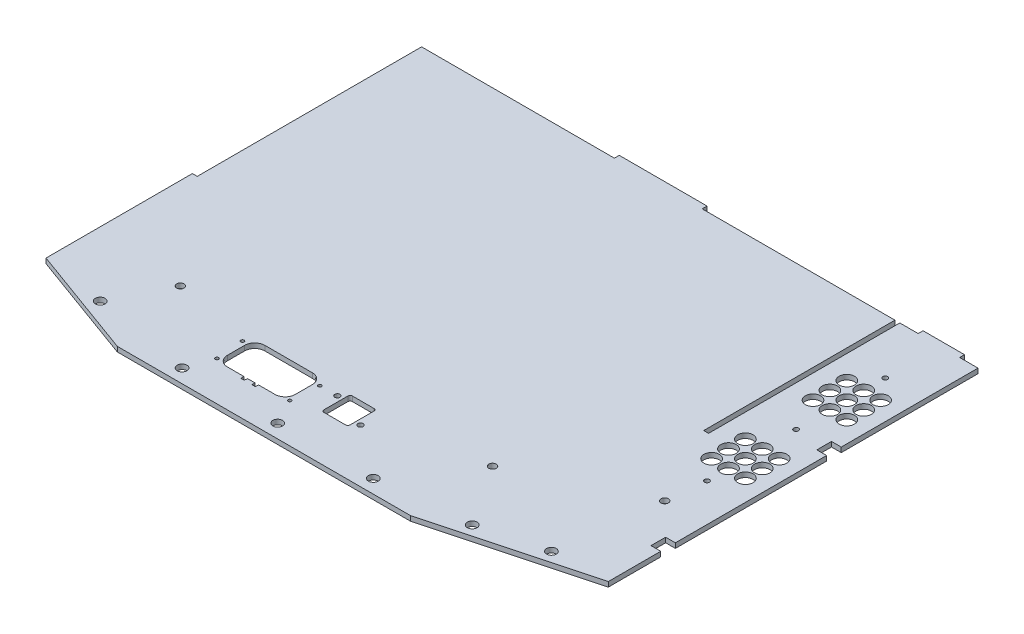
SolidWorks part; units mm, degrees
material "6061-T6 (SS)"
ref_plane "X-Y Datum" through (0, 0, 0) normal (0, 0, 1) x (1, 0, 0)
ref_plane "X-Z Datum" through (0, 0, 0) normal (0, 1, 0) x (1, 0, 0)
ref_plane "Y-Z Datum" through (0, 0, 0) normal (1, 0, 0) x (0, 0, -1)
sketch "Sketch1" plane through (0, 0, 0) normal (0, 0, 1) x (1, 0, 0)
  line L1 (-154.0408, -1.5875) -> (154.0408, -1.5875)
  line L2 (-154.0408, -1.5875) -> (-154.0408, 1.5875)
  line L3 (-154.0408, 1.5875) -> (154.0408, 1.5875)
  line L4 (154.0408, -1.5875) -> (154.0408, 1.5875)
  line L5 (-154.0408, -1.5875) -> (154.0408, 1.5875) construction
  line L6 (-154.0408, 1.5875) -> (154.0408, -1.5875) construction
  point P0 (0, 0)
  dimension "D1" = 3.175
  dimension "D2" = 308.0817
extrude "Boss-Extrude1" add sketch "Sketch1" along normal blind 267.83
sketch "Sketch3" plane through (154.0408, 0, 0) normal (1, 0, 0) x (0, 0, -1)
  line L9 (0, -1.5875) -> (0, 1.5875)
  line L10 (0, 1.5875) -> (-267.83, 1.5875)
  line L11 (-267.83, 1.5875) -> (-267.83, -1.5875)
  line L12 (-267.83, -1.5875) -> (0, -1.5875)
  line L13 (0, -1.5875) -> (0, 1.5875)
  line L14 (0, 1.5875) -> (-267.83, 1.5875)
  line L15 (-267.83, 1.5875) -> (-267.83, -1.5875)
  line L16 (-267.83, -1.5875) -> (0, -1.5875)
  dimension "D1" = 0
extrude "Boss-Extrude3" add sketch "Sketch3" along normal blind 3.175
sketch "Sketch4" plane through (0, 0, 267.83) normal (0, 0, 1) x (1, 0, 0)
  line L1 (157.2158, -1.5875) -> (208.1047, -1.5875)
  line L2 (157.2158, -1.5875) -> (157.2158, 1.5875)
  line L3 (157.2158, 1.5875) -> (208.1047, 1.5875)
  line L4 (208.1047, -1.5875) -> (208.1047, 1.5875)
  dimension "D1" = 3.175
  dimension "D2" = 50.8889
extrude "Boss-Extrude4" add sketch "Sketch4" against normal blind 267.83
sketch "Sketch6" plane through (0, 1.5875, 0) normal (0, 1, 0) x (1, 0, 0)
  line L0 (106.5047, -267.83) -> (106.5047, -228.46)
  line L1 (208.1047, -267.83) -> (-154.0408, -267.83) construction
  line L2 (208.1047, -228.46) -> (106.5047, -228.46)
  line L3 (208.1047, 0) -> (208.1047, -267.83) construction
  line L5 (106.5047, -267.83) -> (208.1047, -240.6064)
  line L7 (208.1047, -228.46) -> (208.1047, -240.6064)
  line L8 (208.1047, 0) -> (208.1047, -267.83) construction
  line L9 (208.1047, -267.83) -> (-154.0408, -267.83) construction
  line M9 (-154.0408, -267.83) -> (208.1047, -267.83)
  line M10 (208.1047, -267.83) -> (208.1047, 0)
  dimension "D1" = 39.37
  dimension "D2" = 101.6
  dimension "D3" = 15
extrude "Cut-Extrude1" cut sketch "Sketch6" against normal through all contours L5 M9 M10
sketch "Sketch19" plane through (0, 1.5875, 0) normal (0, 1, 0) x (1, 0, 0)
  line L0 (208.1047, 0) -> (208.1047, -240.6064) construction
  line L1 (208.1047, 0) -> (-154.0408, 0) construction
  line L3 (164.1047, -82.5) -> (204.1047, -82.5)
  line L4 (164.1047, -82.5) -> (164.1047, -42.5)
  line L5 (164.1047, -42.5) -> (204.1047, -42.5)
  line L6 (204.1047, -82.5) -> (204.1047, -42.5)
  line L7 (164.1047, -82.5) -> (204.1047, -42.5) construction
  line L8 (164.1047, -42.5) -> (204.1047, -82.5) construction
  circle A0 centre (172.4867, -49.7748) radius 5
  dimension "D5" = 10
  dimension "D6" = 7.2748
  dimension "D1" = 40
  dimension "D2" = 40
  dimension "D3" = 42.5
  dimension "D4" = 8.382
  dimension "D7" = 4
extrude "Cut-Extrude5" cut sketch "Sketch19" against normal through all contours A0
pattern_linear "LPattern1" count 3 spacing 11 along (1, 0, 0) of "Cut-Extrude5"
pattern_linear "LPattern2" count 3 spacing 11 along (0, 0, 1) of "LPattern1", "Cut-Extrude5"
pattern_linear "LPattern3" count 2 spacing 66 along (0, 0, 1) of "LPattern2", "Cut-Extrude5", "LPattern1"
sketch "Sketch21" plane through (-154.0408, 0, 0) normal (-1, 0, 0) x (0, 0, 1)
  line L14 (0, -1.5875) -> (267.83, -1.5875)
  line L15 (267.83, -1.5875) -> (267.83, 1.5875)
  line L16 (267.83, 1.5875) -> (0, 1.5875)
  line L17 (0, 1.5875) -> (0, -1.5875)
  line L18 (0, -1.5875) -> (267.83, -1.5875)
  line L20 (267.83, 1.5875) -> (0, 1.5875)
  line L21 (0, 1.5875) -> (0, -1.5875)
  line L22 (267.83, -1.5875) -> (267.83, 1.5875)
  dimension "D1" = 0
extrude "Boss-Extrude5" add sketch "Sketch21" along normal blind 3.175
sketch "Sketch11" plane through (0, -1.5875, 0) normal (0, -1, 0) x (1, 0, 0)
  line L0 (-84.2547, 267.83) -> (-84.2547, 241.2743)
  line L3 (-157.2158, 267.83) -> (106.5047, 267.83) construction
  line L4 (-157.2158, 241.2743) -> (-84.2547, 267.83)
  line L5 (-157.2158, 241.2743) -> (-84.2547, 241.2743)
  line L7 (-157.2158, 0) -> (-157.2158, 267.83) construction
  dimension "D1" = 26.5557
  dimension "D2" = 20
extrude "Cut-Extrude3" cut sketch "Sketch11" against normal through all
sketch "Sketch36" plane through (0, 1.5875, 0) normal (0, 1, 0) x (1, 0, 0)
  circle A1 centre (183.4867, -35.7748) radius 2.4 construction
  circle A2 centre (183.4867, -35.7748) radius 1.5875
  dimension "D1" = 3.175
extrude "Cut-Extrude12" cut sketch "Sketch36" against normal through all both and the other way through all
pattern_linear "LPattern4" count 3 spacing 58 along (0, 0, 1) of "Cut-Extrude12"
sketch "Sketch38" plane through (0, 1.5875, 0) normal (0, 1, 0) x (1, 0, 0)
  point P0 (180.965, -176.776)
  point P1 (105.4291, -213.285)
  point P2 (105.4291, -213.285)
  point P3 (-97.7709, -213.285)
hole_wizard "M4 Clearance Hole1" positions "Sketch38" profile "Sketch39" hole size "M4" standard "ANSI Metric" end condition through all
sketch "Sketch39" plane through (180.965, 1.5875, 176.776) normal (1, 0, 0) x (0, 0, 1)
  line L0 (0, 0) -> (0, 3.175)
  line L1 (0, 3.175) -> (2.4, 3.175)
  line L2 (2.4, 3.175) -> (2.4, 0)
  line L5 (2.4, 0) -> (0, 0)
  line L11 (0, -6.35) -> (0, 107.95) construction
  dimension "Thru Hole Dia." = 4.8
  dimension "Thru Hole Depth" = 3.175
sketch "Sketch40" plane through (0, 1.5875, 0) normal (0, 1, 0) x (1, 0, 0)
  circle A0 centre (172.5447, -242.093) radius 3.175
  circle A1 centre (131.9047, -252.9824) radius 3.175
  circle A2 centre (73.4847, -258.94) radius 3.175
  circle A3 centre (11.2547, -258.94) radius 3.175
  circle A4 centre (-50.9753, -258.94) radius 3.175
  circle A5 centre (-115.3222, -247.9214) radius 3.175
  point P0 (-115.3222, -247.9214)
  point P1 (-50.9753, -258.94)
  point P3 (11.2547, -258.94)
  point P5 (73.4847, -258.94)
  point P7 (131.9047, -252.9824)
  point P9 (172.5447, -242.093)
  dimension "D1" = 6.35
extrude "Cut-Extrude13" cut sketch "Sketch40" against normal through all
sketch "Sketch41" plane through (0, 1.5875, 0) normal (0, 1, 0) x (1, 0, 0)
  line L0 (-25.8051, -243.2308) -> (-25.6301, -245.2308) construction
  line L1 (-25.6301, -245.2308) -> (-24.1801, -245.2308) construction
  line L2 (-24.1801, -245.2308) -> (-24.0051, -243.2308) construction
  line L3 (-18.4301, -245.2308) -> (-16.9801, -245.2308) construction
  line L4 (-16.9801, -245.2308) -> (-16.8051, -243.2308) construction
  line L5 (-18.6051, -243.2308) -> (-18.4301, -245.2308) construction
  line L6 (-16.8051, -243.2308) -> (-5.8051, -243.2308) construction
  line L7 (0.3949, -237.0308) -> (0.3949, -225.8308) construction
  line L8 (-5.8051, -219.6308) -> (-36.8051, -219.6308) construction
  line L9 (-43.0051, -225.8308) -> (-43.0051, -237.0308) construction
  line L10 (-36.8051, -243.2308) -> (-25.8051, -243.2308) construction
  line L11 (-24.0051, -243.2308) -> (-18.6051, -243.2308) construction
  line L12 (-25.8051, -243.2308) -> (-25.6301, -245.2308) construction
  line L13 (-25.6301, -245.2308) -> (-24.1801, -245.2308) construction
  line L14 (-24.1801, -245.2308) -> (-24.0051, -243.2308) construction
  line L15 (-18.4301, -245.2308) -> (-16.9801, -245.2308) construction
  line L16 (-16.9801, -245.2308) -> (-16.8051, -243.2308) construction
  line L17 (-18.6051, -243.2308) -> (-18.4301, -245.2308) construction
  line L18 (-16.8051, -243.2308) -> (-5.8051, -243.2308) construction
  line L19 (0.3949, -237.0308) -> (0.3949, -225.8308) construction
  line L20 (-5.8051, -219.6308) -> (-36.8051, -219.6308) construction
  line L21 (-43.0051, -225.8308) -> (-43.0051, -237.0308) construction
  line L22 (-36.8051, -243.2308) -> (-25.8051, -243.2308) construction
  line L23 (-24.0051, -243.2308) -> (-18.6051, -243.2308) construction
  line L24 (20.242, -220.3508) -> (34.292, -220.3508) construction
  line L25 (34.292, -219.7008) -> (20.242, -219.7008) construction
  line L26 (19.142, -220.8008) -> (19.142, -236.3508) construction
  line L27 (19.792, -236.3508) -> (19.792, -220.8008) construction
  line L28 (20.242, -237.4508) -> (34.292, -237.4508) construction
  line L29 (34.292, -236.8008) -> (20.242, -236.8008) construction
  line L30 (34.742, -220.8008) -> (34.742, -236.3508) construction
  line L31 (35.392, -236.3508) -> (35.392, -220.8008) construction
  line L32 (20.242, -220.3508) -> (34.292, -220.3508) construction
  line L33 (34.292, -219.7008) -> (20.242, -219.7008) construction
  line L34 (19.142, -220.8008) -> (19.142, -236.3508) construction
  line L35 (19.792, -236.3508) -> (19.792, -220.8008) construction
  line L36 (20.242, -237.4508) -> (34.292, -237.4508) construction
  line L37 (34.292, -236.8008) -> (20.242, -236.8008) construction
  line L38 (34.742, -220.8008) -> (34.742, -236.3508) construction
  line L39 (35.392, -236.3508) -> (35.392, -220.8008) construction
  line L40 (15.267, -225.0758) -> (15.267, -223.0758) construction
  line L41 (39.267, -234.0758) -> (39.267, -232.0758) construction
  line L42 (-26.1542, -243.6118) -> (-25.9792, -245.6118)
  line L43 (-25.9792, -245.6118) -> (-23.8309, -245.6118)
  line L44 (-23.8309, -245.6118) -> (-23.656, -243.6118)
  line L45 (-23.656, -243.6118) -> (-18.9542, -243.6118)
  line L46 (-18.9542, -243.6118) -> (-18.7792, -245.6118)
  line L47 (-18.7792, -245.6118) -> (-16.6309, -245.6118)
  line L48 (-16.6309, -245.6118) -> (-16.456, -243.6118)
  line L49 (-16.456, -243.6118) -> (-5.8051, -243.6118)
  line L50 (0.7759, -237.0308) -> (0.7759, -225.8308)
  line L51 (-5.8051, -219.2498) -> (-36.8051, -219.2498)
  line L52 (-43.3861, -225.8308) -> (-43.3861, -237.0308)
  line L53 (-36.8051, -243.6118) -> (-26.1542, -243.6118)
  line L54 (18.761, -220.8008) -> (18.761, -236.3508)
  line L55 (20.242, -237.8318) -> (34.292, -237.8318)
  line L56 (35.773, -236.3508) -> (35.773, -220.8008)
  line L57 (34.292, -219.3198) -> (20.242, -219.3198)
  spline S0 degree 3 poles (-5.8051, -243.2308) (-2.1732, -243.2308) (0.3949, -240.6627) (0.3949, -237.0308) knots 0 0 0 0 1 1 1 1 weights 1 0.804738 0.804738 1 construction
  spline S1 degree 3 poles (0.3949, -225.8308) (0.3949, -222.1989) (-2.1732, -219.6308) (-5.8051, -219.6308) knots 0 0 0 0 1 1 1 1 weights 1 0.804738 0.804738 1 construction
  spline S2 degree 3 poles (-36.8051, -219.6308) (-40.4369, -219.6308) (-43.0051, -222.1989) (-43.0051, -225.8308) knots 0 0 0 0 1 1 1 1 weights 1 0.804738 0.804738 1 construction
  spline S3 degree 3 poles (-43.0051, -237.0308) (-43.0051, -240.6627) (-40.4369, -243.2308) (-36.8051, -243.2308) knots 0 0 0 0 1 1 1 1 weights 1 0.804738 0.804738 1 construction
  spline S4 degree 3 poles (-5.8051, -243.2308) (-2.1732, -243.2308) (0.3949, -240.6627) (0.3949, -237.0308) knots 0 0 0 0 1 1 1 1 weights 1 0.804738 0.804738 1 construction
  spline S5 degree 3 poles (0.3949, -225.8308) (0.3949, -222.1989) (-2.1732, -219.6308) (-5.8051, -219.6308) knots 0 0 0 0 1 1 1 1 weights 1 0.804738 0.804738 1 construction
  spline S6 degree 3 poles (-36.8051, -219.6308) (-40.4369, -219.6308) (-43.0051, -222.1989) (-43.0051, -225.8308) knots 0 0 0 0 1 1 1 1 weights 1 0.804738 0.804738 1 construction
  spline S7 degree 3 poles (-43.0051, -237.0308) (-43.0051, -240.6627) (-40.4369, -243.2308) (-36.8051, -243.2308) knots 0 0 0 0 1 1 1 1 weights 1 0.804738 0.804738 1 construction
  spline S8 degree 3 poles (34.292, -220.3508) (34.5556, -220.3508) (34.742, -220.5372) (34.742, -220.8008) knots 0 0 0 0 1 1 1 1 weights 1 0.804738 0.804738 1 construction
  spline S9 degree 3 poles (35.392, -220.8008) (35.392, -220.1564) (34.9364, -219.7008) (34.292, -219.7008) knots 0 0 0 0 1 1 1 1 weights 1 0.804738 0.804738 1 construction
  spline S10 degree 3 poles (20.242, -219.7008) (19.5976, -219.7008) (19.142, -220.1564) (19.142, -220.8008) knots 0 0 0 0 1 1 1 1 weights 1 0.804738 0.804738 1 construction
  spline S11 degree 3 poles (19.792, -220.8008) (19.792, -220.5372) (19.9784, -220.3508) (20.242, -220.3508) knots 0 0 0 0 1 1 1 1 weights 1 0.804738 0.804738 1 construction
  spline S12 degree 3 poles (19.142, -236.3508) (19.142, -236.9952) (19.5976, -237.4508) (20.242, -237.4508) knots 0 0 0 0 1 1 1 1 weights 1 0.804738 0.804738 1 construction
  spline S13 degree 3 poles (20.242, -236.8008) (19.9784, -236.8008) (19.792, -236.6144) (19.792, -236.3508) knots 0 0 0 0 1 1 1 1 weights 1 0.804738 0.804738 1 construction
  spline S14 degree 3 poles (34.292, -237.4508) (34.9364, -237.4508) (35.392, -236.9952) (35.392, -236.3508) knots 0 0 0 0 1 1 1 1 weights 1 0.804738 0.804738 1 construction
  spline S15 degree 3 poles (34.742, -236.3508) (34.742, -236.6144) (34.5556, -236.8008) (34.292, -236.8008) knots 0 0 0 0 1 1 1 1 weights 1 0.804738 0.804738 1 construction
  spline S16 degree 3 poles (34.292, -220.3508) (34.5556, -220.3508) (34.742, -220.5372) (34.742, -220.8008) knots 0 0 0 0 1 1 1 1 weights 1 0.804738 0.804738 1 construction
  spline S17 degree 3 poles (35.392, -220.8008) (35.392, -220.1564) (34.9364, -219.7008) (34.292, -219.7008) knots 0 0 0 0 1 1 1 1 weights 1 0.804738 0.804738 1 construction
  spline S18 degree 3 poles (20.242, -219.7008) (19.5976, -219.7008) (19.142, -220.1564) (19.142, -220.8008) knots 0 0 0 0 1 1 1 1 weights 1 0.804738 0.804738 1 construction
  spline S19 degree 3 poles (19.792, -220.8008) (19.792, -220.5372) (19.9784, -220.3508) (20.242, -220.3508) knots 0 0 0 0 1 1 1 1 weights 1 0.804738 0.804738 1 construction
  spline S20 degree 3 poles (19.142, -236.3508) (19.142, -236.9952) (19.5976, -237.4508) (20.242, -237.4508) knots 0 0 0 0 1 1 1 1 weights 1 0.804738 0.804738 1 construction
  spline S21 degree 3 poles (20.242, -236.8008) (19.9784, -236.8008) (19.792, -236.6144) (19.792, -236.3508) knots 0 0 0 0 1 1 1 1 weights 1 0.804738 0.804738 1 construction
  spline S22 degree 3 poles (34.292, -237.4508) (34.9364, -237.4508) (35.392, -236.9952) (35.392, -236.3508) knots 0 0 0 0 1 1 1 1 weights 1 0.804738 0.804738 1 construction
  spline S23 degree 3 poles (34.742, -236.3508) (34.742, -236.6144) (34.5556, -236.8008) (34.292, -236.8008) knots 0 0 0 0 1 1 1 1 weights 1 0.804738 0.804738 1 construction
  spline S24 degree 3 poles (-47.5901, -224.1308) (-47.5901, -221.9608) (-45.4201, -221.9608) (-45.4201, -224.1308) knots 0 0 0 0 1 1 1 1 weights 1 0.333333 0.333333 1 construction
  spline S25 degree 3 poles (-45.4201, -224.1308) (-45.4201, -226.3008) (-47.5901, -226.3008) (-47.5901, -224.1308) knots 0 0 0 0 1 1 1 1 weights 1 0.333333 0.333333 1 construction
  spline S26 degree 3 poles (-43.9201, -242.2308) (-43.9201, -244.4008) (-46.0901, -244.4008) (-46.0901, -242.2308) knots 0 0 0 0 1 1 1 1 weights 1 0.333333 0.333333 1 construction
  spline S27 degree 3 poles (-46.0901, -242.2308) (-46.0901, -240.0608) (-43.9201, -240.0608) (-43.9201, -242.2308) knots 0 0 0 0 1 1 1 1 weights 1 0.333333 0.333333 1 construction
  spline S28 degree 3 poles (3.4799, -242.2308) (3.4799, -244.4008) (1.3099, -244.4008) (1.3099, -242.2308) knots 0 0 0 0 1 1 1 1 weights 1 0.333333 0.333333 1 construction
  spline S29 degree 3 poles (1.3099, -242.2308) (1.3099, -240.0608) (3.4799, -240.0608) (3.4799, -242.2308) knots 0 0 0 0 1 1 1 1 weights 1 0.333333 0.333333 1 construction
  spline S30 degree 3 poles (4.9799, -224.1308) (4.9799, -226.3008) (2.8099, -226.3008) (2.8099, -224.1308) knots 0 0 0 0 1 1 1 1 weights 1 0.333333 0.333333 1 construction
  spline S31 degree 3 poles (2.8099, -224.1308) (2.8099, -221.9608) (4.9799, -221.9608) (4.9799, -224.1308) knots 0 0 0 0 1 1 1 1 weights 1 0.333333 0.333333 1 construction
  spline S32 degree 3 poles (-47.5901, -224.1308) (-47.5901, -221.9608) (-45.4201, -221.9608) (-45.4201, -224.1308) knots 0 0 0 0 1 1 1 1 weights 1 0.333333 0.333333 1
  spline S33 degree 3 poles (-45.4201, -224.1308) (-45.4201, -226.3008) (-47.5901, -226.3008) (-47.5901, -224.1308) knots 0 0 0 0 1 1 1 1 weights 1 0.333333 0.333333 1
  spline S34 degree 3 poles (-43.9201, -242.2308) (-43.9201, -244.4008) (-46.0901, -244.4008) (-46.0901, -242.2308) knots 0 0 0 0 1 1 1 1 weights 1 0.333333 0.333333 1
  spline S35 degree 3 poles (-46.0901, -242.2308) (-46.0901, -240.0608) (-43.9201, -240.0608) (-43.9201, -242.2308) knots 0 0 0 0 1 1 1 1 weights 1 0.333333 0.333333 1
  spline S36 degree 3 poles (3.4799, -242.2308) (3.4799, -244.4008) (1.3099, -244.4008) (1.3099, -242.2308) knots 0 0 0 0 1 1 1 1 weights 1 0.333333 0.333333 1
  spline S37 degree 3 poles (1.3099, -242.2308) (1.3099, -240.0608) (3.4799, -240.0608) (3.4799, -242.2308) knots 0 0 0 0 1 1 1 1 weights 1 0.333333 0.333333 1
  spline S38 degree 3 poles (4.9799, -224.1308) (4.9799, -226.3008) (2.8099, -226.3008) (2.8099, -224.1308) knots 0 0 0 0 1 1 1 1 weights 1 0.333333 0.333333 1
  spline S39 degree 3 poles (2.8099, -224.1308) (2.8099, -221.9608) (4.9799, -221.9608) (4.9799, -224.1308) knots 0 0 0 0 1 1 1 1 weights 1 0.333333 0.333333 1
  spline S40 degree 3 poles (15.267, -225.0758) (17.267, -225.0758) (17.267, -223.0758) (15.267, -223.0758) knots 0 0 0 0 1 1 1 1 weights 1 0.333333 0.333333 1 construction
  spline S41 degree 3 poles (15.267, -223.0758) (13.267, -223.0758) (13.267, -225.0758) (15.267, -225.0758) knots 0 0 0 0 1 1 1 1 weights 1 0.333333 0.333333 1 construction
  spline S42 degree 3 poles (15.267, -225.0758) (17.267, -225.0758) (17.267, -223.0758) (15.267, -223.0758) knots 0 0 0 0 1 1 1 1 weights 1 0.333333 0.333333 1 construction
  spline S43 degree 3 poles (15.267, -223.0758) (13.267, -223.0758) (13.267, -225.0758) (15.267, -225.0758) knots 0 0 0 0 1 1 1 1 weights 1 0.333333 0.333333 1 construction
  spline S44 degree 3 poles (39.267, -234.0758) (41.267, -234.0758) (41.267, -232.0758) (39.267, -232.0758) knots 0 0 0 0 1 1 1 1 weights 1 0.333333 0.333333 1 construction
  spline S45 degree 3 poles (39.267, -232.0758) (37.267, -232.0758) (37.267, -234.0758) (39.267, -234.0758) knots 0 0 0 0 1 1 1 1 weights 1 0.333333 0.333333 1 construction
  spline S46 degree 3 poles (39.267, -234.0758) (41.267, -234.0758) (41.267, -232.0758) (39.267, -232.0758) knots 0 0 0 0 1 1 1 1 weights 1 0.333333 0.333333 1 construction
  spline S47 degree 3 poles (39.267, -232.0758) (37.267, -232.0758) (37.267, -234.0758) (39.267, -234.0758) knots 0 0 0 0 1 1 1 1 weights 1 0.333333 0.333333 1 construction
  spline S48 degree 1 poles (-5.8051, -243.6118) (0.7759, -237.0308) knots 0 0 1 1 construction
  spline S49 degree 1 poles (0.7759, -225.8308) (-5.8051, -219.2498) knots 0 0 1 1 construction
  spline S50 degree 1 poles (-36.8051, -219.2498) (-43.3861, -225.8308) knots 0 0 1 1 construction
  spline S51 degree 1 poles (-43.3861, -237.0308) (-36.8051, -243.6118) knots 0 0 1 1 construction
  spline S52 degree 3 poles (-5.8051, -243.6118) (-5.4042, -243.6118) (-4.6186, -243.5426) (-2.9592, -243.079) (-1.014, -241.8219) (0.2432, -239.8767) (0.7067, -238.2173) (0.7759, -237.4316) (0.7759, -237.0308) knots 0 0 0 0 0.125 0.25 0.5 0.75 0.875 1 1 1 1
  spline S53 degree 3 poles (0.7759, -225.8308) (0.7759, -225.43) (0.7067, -224.6443) (0.2432, -222.9849) (-1.014, -221.0397) (-2.9592, -219.7826) (-4.6186, -219.319) (-5.4042, -219.2498) (-5.8051, -219.2498) knots 0 0 0 0 0.125 0.25 0.5 0.75 0.875 1 1 1 1
  spline S54 degree 3 poles (-36.8051, -219.2498) (-37.2059, -219.2498) (-37.9916, -219.319) (-39.651, -219.7826) (-41.5961, -221.0397) (-42.8533, -222.9849) (-43.3168, -224.6443) (-43.3861, -225.43) (-43.3861, -225.8308) knots 0 0 0 0 0.125 0.25 0.5 0.75 0.875 1 1 1 1
  spline S55 degree 3 poles (-43.3861, -237.0308) (-43.3861, -237.4316) (-43.3168, -238.2173) (-42.8533, -239.8767) (-41.5961, -241.8219) (-39.651, -243.079) (-37.9916, -243.5426) (-37.2059, -243.6118) (-36.8051, -243.6118) knots 0 0 0 0 0.125 0.25 0.5 0.75 0.875 1 1 1 1
  spline S56 degree 1 poles (18.761, -236.3508) (20.242, -237.8318) knots 0 0 1 1 construction
  spline S57 degree 1 poles (34.292, -237.8318) (35.773, -236.3508) knots 0 0 1 1 construction
  spline S58 degree 3 poles (18.761, -236.3508) (18.761, -236.5358) (18.8246, -236.8976) (19.1622, -237.4306) (19.6953, -237.7682) (20.057, -237.8318) (20.242, -237.8318) knots 0 0 0 0 0.25 0.5 0.75 1 1 1 1
  spline S59 degree 3 poles (34.292, -237.8318) (34.477, -237.8318) (34.8387, -237.7682) (35.3718, -237.4306) (35.7094, -236.8976) (35.773, -236.5358) (35.773, -236.3508) knots 0 0 0 0 0.25 0.5 0.75 1 1 1 1
  spline S60 degree 1 poles (35.773, -220.8008) (34.292, -219.3198) knots 0 0 1 1 construction
  spline S61 degree 1 poles (20.242, -219.3198) (18.761, -220.8008) knots 0 0 1 1 construction
  spline S62 degree 3 poles (35.773, -220.8008) (35.773, -220.6158) (35.7094, -220.2541) (35.3718, -219.721) (34.8387, -219.3834) (34.477, -219.3198) (34.292, -219.3198) knots 0 0 0 0 0.25 0.5 0.75 1 1 1 1
  spline S63 degree 3 poles (20.242, -219.3198) (20.057, -219.3198) (19.6953, -219.3834) (19.1622, -219.721) (18.8246, -220.2541) (18.761, -220.6158) (18.761, -220.8008) knots 0 0 0 0 0.25 0.5 0.75 1 1 1 1
  point P40 (39.267, -233.0758)
  point P44 (15.267, -224.0758)
  dimension "D1" = 0.381
  dimension "D2" = 0.381
  dimension "D3" = 0.381
extrude "Cut-Extrude15" cut sketch "Sketch41" against normal through all contours L57 S63 L54 S58 L55 S59 L56 S62 | L52 S55 L53 L42 L43 L44 L45 L46 L47 L48 L49 S52 L50 S53 L51 S54 | S37 S36 | S39 S38 | S35 S34 | S33 S32
hole_wizard "M3 Clearance Hole1" positions "Sketch44" profile "Sketch43" hole size "M3" standard "ANSI Metric" end condition through all
sketch "Sketch44" plane through (0, 1.5875, 0) normal (0, 1, 0) x (1, 0, 0)
  point P0 (39.267, -233.0758)
  point P3 (15.267, -224.0758)
sketch "Sketch43" plane through (39.267, 1.5875, 233.0758) normal (1, 0, 0) x (0, 0, 1)
  line L0 (0, 0) -> (0, 3.175)
  line L1 (0, 3.175) -> (1.7, 3.175)
  line L2 (1.7, 3.175) -> (1.7, 0)
  line L5 (1.7, 0) -> (0, 0)
  line L11 (0, -6.35) -> (0, 107.95) construction
  dimension "Thru Hole Dia." = 3.4
  dimension "Thru Hole Depth" = 3.175
sketch "Sketch45" plane through (0, 0, 0) normal (0, 0, -1) x (-1, 0, 0)
  line L0 (28.6512, -1.6727) -> (-28.6512, -1.6727) construction
  line L1 (0, -1.5875) -> (0, 1.5875) construction
  line L2 (157.2158, -1.5875) -> (-208.1047, -1.5875) construction
  line L3 (-208.1047, 1.5875) -> (157.2158, 1.5875) construction
  line L4 (-169.0911, -1.6637) -> (-196.231, -1.6637) construction
  line L5 (-28.575, 1.5875) -> (28.575, 1.5875)
  line L6 (-28.575, 1.5875) -> (-28.575, -1.5875)
  line L7 (-28.575, -1.5875) -> (28.575, -1.5875)
  line L8 (28.575, 1.5875) -> (28.575, -1.5875)
  line L9 (-28.575, 1.5875) -> (28.575, -1.5875) construction
  line L10 (-28.575, -1.5875) -> (28.575, 1.5875) construction
  line L11 (-182.661, -1.5875) -> (-182.661, 1.5875) construction
  line L12 (-157.216, -1.5875) -> (-195.316, -1.5875) construction
  line L13 (-170.9867, 1.5875) -> (-195.9867, 1.5875) construction
  line L15 (-196.1548, 1.5875) -> (-169.1673, 1.5875)
  line L16 (-196.1548, 1.5875) -> (-196.1548, -1.5875)
  line L17 (-196.1548, -1.5875) -> (-169.1673, -1.5875)
  line L18 (-169.1673, 1.5875) -> (-169.1673, -1.5875)
  line L19 (-196.1548, 1.5875) -> (-169.1673, -1.5875) construction
  line L20 (-196.1548, -1.5875) -> (-169.1673, 1.5875) construction
  point P0 (0, -1.6727)
  point P10 (0, 0)
  point P15 (-182.661, -1.6637)
  point P24 (-182.661, 0)
  dimension "D1" = 57.15
  dimension "D2" = 26.9875
extrude "Boss-Extrude6" add sketch "Sketch45" along normal blind 3.175
sketch "Sketch46" plane through (0, 1.5875, 0) normal (0, 1, 0) x (1, 0, 0)
  line L0 (154.041, -124.442) -> (157.216, -124.442) construction
  line L1 (154.041, -124.442) -> (154.041, -50.8) construction
  line L2 (157.216, -124.442) -> (157.216, -50.8) construction
  line L3 (154.041, -124.442) -> (157.216, -124.442)
  line L4 (154.041, -124.442) -> (154.041, 0)
  line L5 (157.216, -124.442) -> (157.216, 0)
  line L6 (169.1673, 0) -> (28.575, 0) construction
  line L7 (154.041, 0) -> (157.216, 0)
  line L8 (153.9648, -124.5182) -> (153.9648, 0.0762)
  line L9 (153.9648, 0.0762) -> (157.2922, 0.0762)
  line L10 (157.2922, -124.5182) -> (157.2922, 0.0762)
  line L11 (153.9648, -124.5182) -> (157.2922, -124.5182)
  dimension "D1" = 0.0762
extrude "Cut-Extrude16" cut sketch "Sketch46" against normal through all contours L7 L4 L3 L5
sketch "Sketch47" plane through (0, 1.5875, 0) normal (0, 1, 0) x (1, 0, 0)
  line L0 (-157.292, -146.1005) -> (-153.9646, -146.1005)
  line L1 (-157.2158, 0) -> (-154.0408, 0)
  line L2 (-157.2158, 0) -> (-157.2158, -146.0243)
  line L3 (-157.2158, -146.0243) -> (-154.0408, -146.0243)
  line L4 (-154.0408, 0) -> (-154.0408, -146.0243)
  line L5 (-153.9646, 0.0762) -> (-153.9646, -146.1005)
  line L6 (-157.292, 0.0762) -> (-153.9646, 0.0762)
  line L7 (-157.292, 0.0762) -> (-157.292, -146.1005)
  dimension "D1" = 3.175
  dimension "D2" = 95.25
  dimension "D3" = 0.0762
extrude "Cut-Extrude17" cut sketch "Sketch47" against normal through all contours L4 L1 L2 L3
sketch "Sketch48" plane through (0, 1.5875, 0) normal (0, 1, 0) x (1, 0, 0)
  line L0 (208.1809, -196.8861) -> (201.6785, -196.8861)
  line L1 (201.6785, -196.8861) -> (201.6785, -206.5635)
  line L2 (201.6785, -206.5635) -> (208.1809, -206.5635)
  line L3 (208.1809, -206.5635) -> (208.1809, -196.8861)
  line L4 (201.7547, -196.9623) -> (201.7547, -206.4873)
  line L5 (201.7547, -206.4873) -> (208.1047, -206.4873)
  line L6 (208.1047, -206.4873) -> (208.1047, -196.9623)
  line L7 (208.1047, -196.9623) -> (201.7547, -196.9623)
  line L8 (201.7547, -196.9623) -> (201.7547, -206.4873)
  line L9 (201.7547, -206.4873) -> (208.1047, -206.4873)
  line L10 (208.1047, -206.4873) -> (208.1047, -196.9623)
  line L11 (208.1047, -196.9623) -> (201.7547, -196.9623)
  line L12 (201.7547, -89.0123) -> (201.7547, -98.5373)
  line L13 (201.7547, -98.5373) -> (208.1047, -98.5373)
  line L14 (208.1047, -98.5373) -> (208.1047, -89.0123)
  line L15 (208.1047, -89.0123) -> (201.7547, -89.0123)
  line L16 (201.7547, -89.0123) -> (201.7547, -98.5373)
  line L17 (201.7547, -98.5373) -> (208.1047, -98.5373)
  line L18 (208.1047, -98.5373) -> (208.1047, -89.0123)
  line L19 (208.1047, -89.0123) -> (201.7547, -89.0123)
  line L20 (201.6785, -98.6135) -> (208.1809, -98.6135)
  line L21 (208.1809, -98.6135) -> (208.1809, -88.9361)
  line L22 (208.1809, -88.9361) -> (201.6785, -88.9361)
  line L23 (201.6785, -88.9361) -> (201.6785, -98.6135)
  dimension "D1" = 0
  dimension "D2" = 0
  dimension "D3" = 0.0762
extrude "Cut-Extrude18" cut sketch "Sketch48" against normal through all contours L16 L17 L18 L19 | L8 L9 L10 L11
